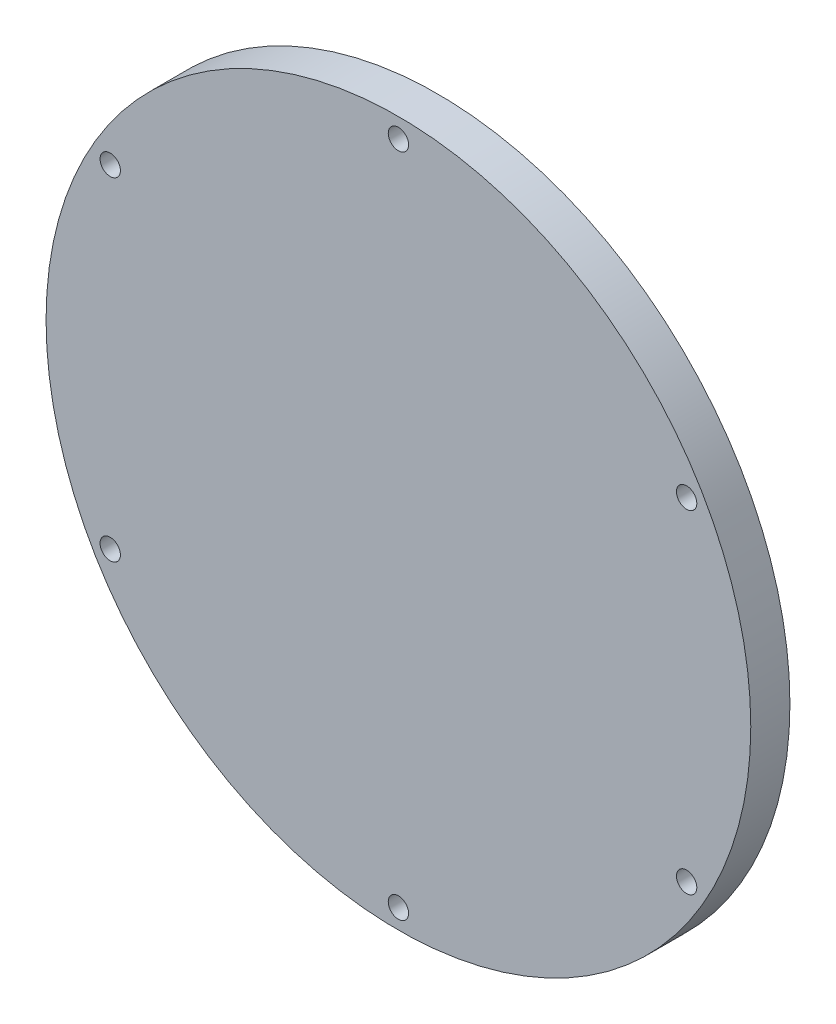
SolidWorks part; units mm, degrees
ref_plane "前视基准面" through (0, 0, 0) normal (0, 0, 1) x (1, 0, 0)
ref_plane "上视基准面" through (0, 0, 0) normal (0, 1, 0) x (1, 0, 0)
ref_plane "右视基准面" through (0, 0, 0) normal (1, 0, 0) x (0, 0, -1)
sketch "草图1" plane through (0, 0, 0) normal (0, 0, 1) x (1, 0, 0)
  circle A0 centre (0, 0) radius 57.15
  dimension "D1" = 114.3
extrude "凸台-拉伸1" add sketch "草图1" along normal blind 6.35
sketch "草图2" plane through (0, 0, 0) normal (0, 0, -1) x (-1, 0, 0)
  circle A0 centre (-46.7437, 26.9875) radius 1.651
  circle A1 centre (0, 53.975) radius 1.651
  circle A2 centre (46.7437, 26.9875) radius 1.651
  circle A3 centre (46.7437, -26.9875) radius 1.651
  circle A4 centre (0, -53.975) radius 1.651
  circle A5 centre (-46.7437, -26.9875) radius 1.651
  point P15 (0, 0)
  dimension "D1" = 3.302
  dimension "D3" = 53.975
  dimension "D2" = 6
extrude "切除-拉伸1" cut sketch "草图2" against normal through all
